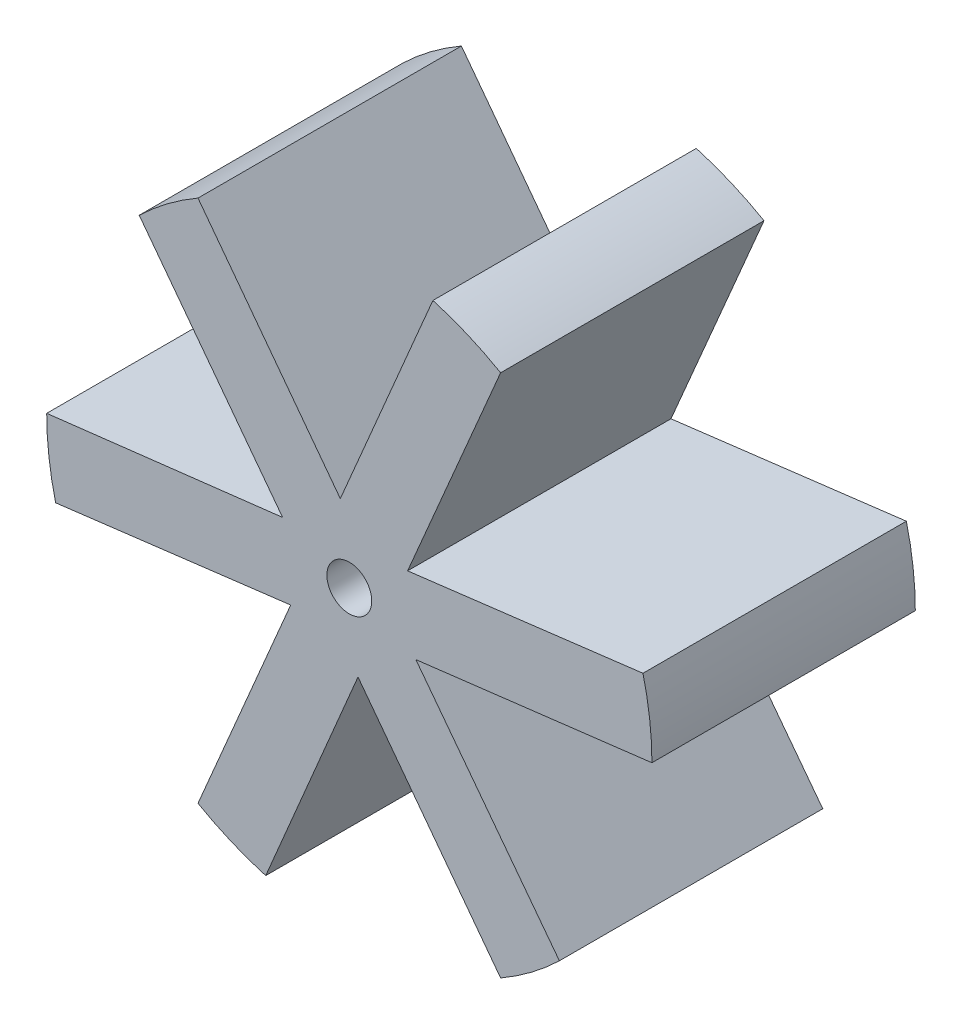
SolidWorks part; units mm, degrees
material "ABS"
ref_plane "前视基准面" through (0, 0, 0) normal (0, 0, 1) x (1, 0, 0)
ref_plane "上视基准面" through (0, 0, 0) normal (0, 1, 0) x (1, 0, 0)
ref_plane "右视基准面" through (0, 0, 0) normal (1, 0, 0) x (0, 0, -1)
sketch "草图1" plane through (0, 0, 0) normal (0, 0, 1) x (1, 0, 0)
  line L12 (-18.744, 19.4335) -> (-5.9531, 2.4835)
  line L13 (-13.5, 23.3827) -> (-0.8024, 6.5057)
  line L14 (7.4579, 25.9496) -> (-0.8024, 6.5057)
  line L15 (13.5, 23.3827) -> (5.201, 3.928)
  line L16 (26.2019, 6.5161) -> (5.201, 3.928)
  line L17 (27, 0) -> (5.9382, -2.5604)
  line L18 (18.744, -19.4335) -> (5.9382, -2.5604)
  line L19 (13.5, -23.3827) -> (0.7755, -6.4859)
  line L20 (-7.4579, -25.9496) -> (0.7755, -6.4859)
  line L21 (-13.5, -23.3827) -> (-5.2285, -3.9283)
  line L22 (-27, 0) -> (-5.9531, 2.4835)
  line L23 (-26.2019, -6.5161) -> (-5.2285, -3.9283)
  arc A0 (-27, 0) -> (-26.2019, -6.5161) centre (0, 0) ccw
  arc A13 (13.5, -23.3827) -> (18.744, -19.4335) centre (0, 0) ccw
  arc A17 (-13.5, -23.3827) -> (-7.4579, -25.9496) centre (0, 0) ccw
  arc A18 (13.5, 23.3827) -> (7.4579, 25.9496) centre (0, 0) ccw
  arc A19 (27, 0) -> (26.2019, 6.5161) centre (0, 0) ccw
  arc A20 (0, -3.2823) -> (0.0074, -3.2823) centre (0, 0) ccw
  arc A21 (-13.5, 23.3827) -> (-18.744, 19.4335) centre (0, 0) ccw
  dimension "D1" = 6.5648
extrude "凸台-拉伸1" add sketch "草图1" along normal blind 23.5
sketch "草图2" plane through (0, 0, 23.5) normal (0, 0, 1) x (1, 0, 0)
  circle A0 centre (0, 0) radius 2
extrude "切除-拉伸1" cut sketch "草图2" against normal through all both and the other way through all
